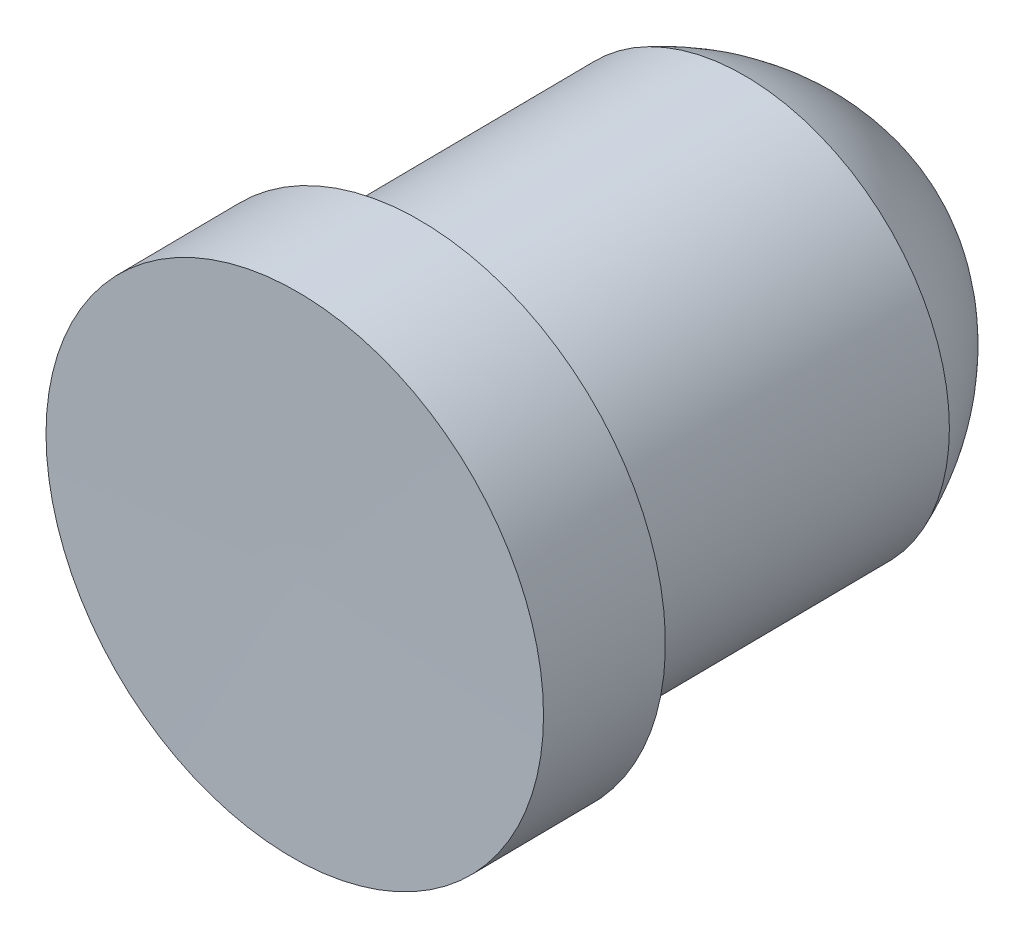
SolidWorks part; units mm, degrees
ref_plane "Front Plane" through (0, 0, 0) normal (0, 0, 1) x (1, 0, 0)
ref_plane "Top Plane" through (0, 0, 0) normal (0, 1, 0) x (1, 0, 0)
ref_plane "Right Plane" through (0, 0, 0) normal (1, 0, 0) x (0, 0, -1)
sketch "Sketch3" plane through (0, 0, 0) normal (0, 1, 0) x (1, 0, 0)
  line L0 (2.7026, 38.6416) -> (2.8616, 23.0316) construction
  line L2 (2.8105, 28.0463) -> (5.8107, 28.045)
  line L3 (5.8107, 28.045) -> (5.7954, 29.545)
  line L4 (5.7954, 29.545) -> (5.2954, 29.5452)
  line L5 (5.2954, 29.5452) -> (5.2547, 33.545)
  line L8 (2.8105, 28.0463) -> (2.7345, 35.5145)
  arc A0 (5.2547, 33.545) -> (2.7345, 35.5145) centre (2.2524, 32.3005) ccw
  dimension "D1" = 5
  dimension "D2" = 4
  dimension "D3" = 6
  dimension "D4" = 1.5
revolve "Revolve1" add sketch "Sketch3" angle 360 about L0
